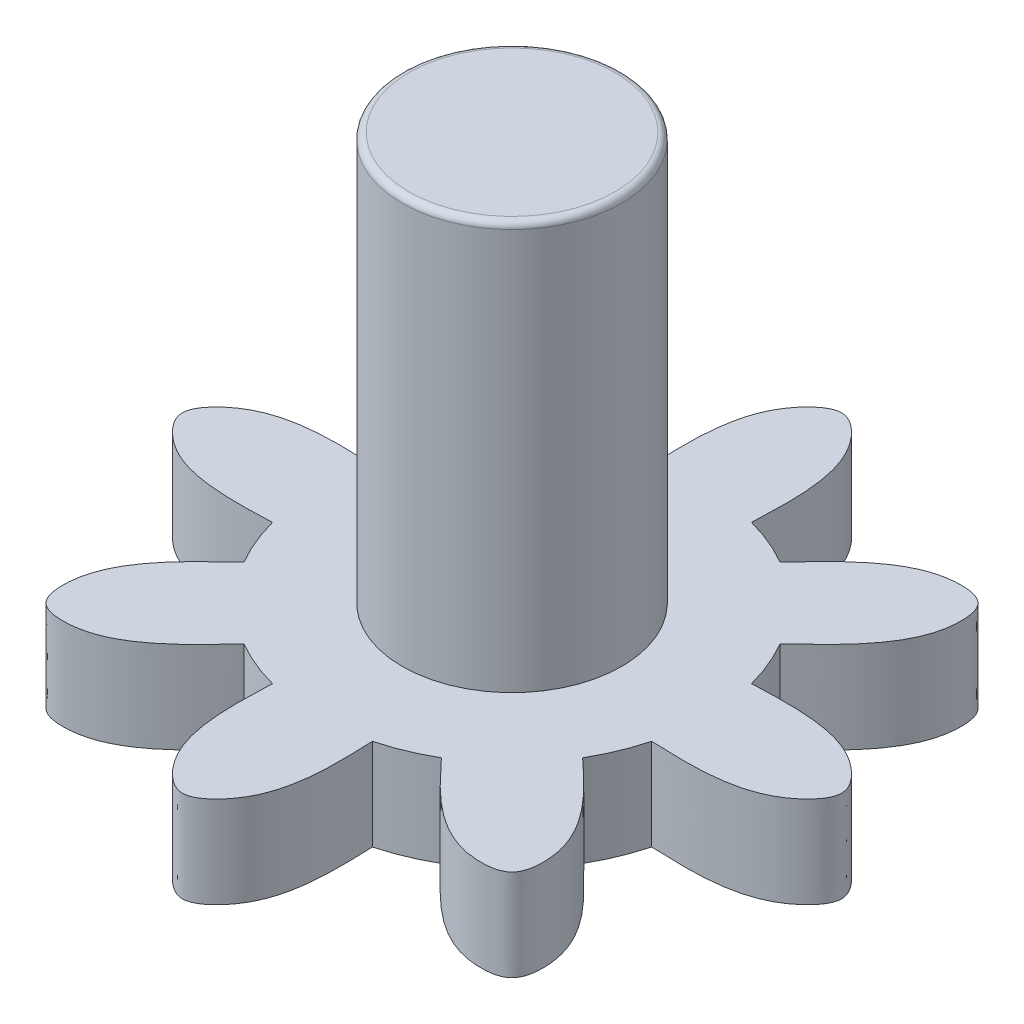
SolidWorks part; units mm, degrees
ref_plane "Front Plane" through (0, 0, 0) normal (0, 0, 1) x (1, 0, 0)
ref_plane "Top Plane" through (0, 0, 0) normal (0, 1, 0) x (1, 0, 0)
ref_plane "Right Plane" through (0, 0, 0) normal (1, 0, 0) x (0, 0, -1)
sketch "Sketch1" plane through (0, 0, 0) normal (0, 1, 0) x (1, 0, 0)
  circle A0 centre (0, 0) radius 5.89
  dimension "D1" = 11.78
extrude "Boss-Extrude1" add sketch "Sketch1" along normal blind 2.75 contours A0
sketch "Sketch3" plane through (0, 0, 0) normal (0, -1, 0) x (1, 0, 0)
  line L0 (-1.5, -5.69) -> (1.5, -5.69)
  line L1 (0, -9.9) -> (0, -5.69) construction
  line L2 (-1.5, -7.39) -> (1.5, -7.39) construction
  spline S0 degree 3 poles (1.5, -5.69) (1.5225, -6.2553) (1.5748, -7.5708) (1.198, -9.1821) (0, -10.089) (-1.198, -9.1821) (-1.5748, -7.5708) (-1.5225, -6.2553) (-1.5, -5.69) knots 0 0 0 0 0.178467 0.415362 0.5 0.584638 0.821533 1 1 1 1
  point P2 (0, -7.795)
  dimension "D1" = 3
  dimension "D2" = 3
  dimension "D3" = 9.9
  dimension "D4" = 1.4
  dimension "D5" = 0.4
  dimension "D6" = 0.7
  dimension "D7" = 1.7
  dimension "D8" = 4.21
extrude "Boss-Extrude2" add sketch "Sketch3" against normal blind 2.75 contours S0 L0
sketch "Sketch4" plane through (0, 2.75, 0) normal (0, 1, 0) x (1, 0, 0)
  circle A0 centre (0, 0) radius 3.3
  dimension "D1" = 6.6
extrude "Boss-Extrude3" add sketch "Sketch4" along normal blind 12.25
pattern_circular "CirPattern1" count 8 over 360 about axis through (0, 0, 0) along (0, 1, 0) of "Boss-Extrude2"
fillet "Fillet1" radius 0.2 1 edges at (0, 15, 3.3)
